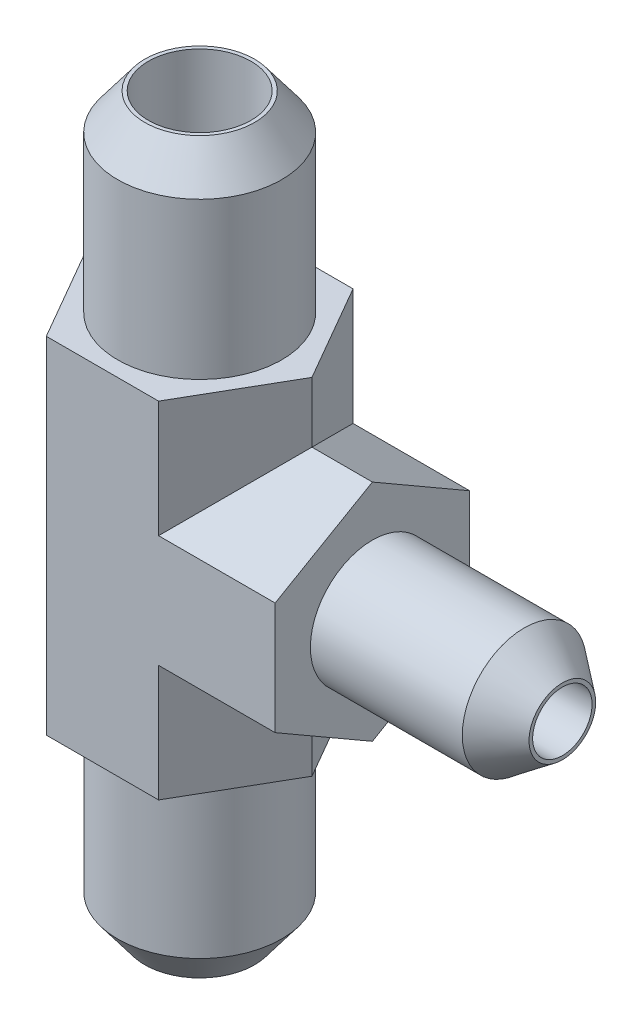
SolidWorks part; units mm, degrees
ref_plane "Front Plane" through (0, 0, 0) normal (0, 0, 1) x (1, 0, 0)
ref_plane "Top Plane" through (0, 0, 0) normal (0, 1, 0) x (1, 0, 0)
ref_plane "Right Plane" through (0, 0, 0) normal (1, 0, 0) x (0, 0, -1)
sketch "Sketch1" plane through (0, 0, 0) normal (0, 1, 0) x (1, 0, 0)
  line L1 (-8.2562, 0) -> (-4.1281, -7.1501)
  line L2 (-4.1281, -7.1501) -> (4.1281, -7.1501)
  line L3 (4.1281, -7.1501) -> (8.2562, 0)
  line L4 (8.2562, 0) -> (4.1281, 7.1501)
  line L5 (4.1281, 7.1501) -> (-4.1281, 7.1501)
  line L6 (-4.1281, 7.1501) -> (-8.2562, 0)
  circle A0 centre (0, 0) radius 7.1501 construction
  dimension "D1" = 14.3002
extrude "Boss-Extrude1" add sketch "Sketch1" along normal mid plane 25.4
sketch "Sketch2" plane through (0, 0, 0) normal (1, 0, 0) x (0, 0, -1)
  line L0 (-7.1501, 12.7) -> (-7.1501, -12.7) construction
  line L1 (0, 8.2562) -> (-7.1501, 4.1281)
  line L2 (-7.1501, 4.1281) -> (-7.1501, -4.1281)
  line L3 (-7.1501, -4.1281) -> (0, -8.2562)
  line L4 (0, -8.2562) -> (7.1501, -4.1281)
  line L5 (7.1501, -4.1281) -> (7.1501, 4.1281)
  line L6 (7.1501, 4.1281) -> (0, 8.2562)
  circle A0 centre (0, 0) radius 7.1501 construction
extrude "Boss-Extrude2" add sketch "Sketch2" along normal blind 12.7
sketch "Sketch3" plane through (12.7, 0, 0) normal (1, 0, 0) x (0, 0, -1)
  circle A0 centre (0, 0) radius 4.5593
  dimension "D1" = 9.1186
extrude "Boss-Extrude3" add sketch "Sketch3" along normal blind 13.97
sketch "Sketch4" plane through (26.67, 0, 0) normal (1, 0, 0) x (0, 0, -1)
  circle A0 centre (0, 0) radius 2.4511
  circle A1 centre (0, 0) radius 11.3639
  dimension "D1" = 4.9022
extrude "Cut-Extrude1" cut sketch "Sketch4" against normal through all draft 37
sketch "Sketch5" plane through (0, -12.7, 0) normal (0, -1, 0) x (1, 0, 0)
  circle A0 centre (0, 0) radius 6.0325
  dimension "D1" = 12.065
extrude "Boss-Extrude4" add sketch "Sketch5" along normal blind 14.1224
sketch "Sketch6" plane through (0, -26.8224, 0) normal (0, -1, 0) x (1, 0, 0)
  circle A0 centre (0, 0) radius 4.0386
  circle A1 centre (0, 0) radius 16.7971
  dimension "D1" = 8.0772
extrude "Cut-Extrude2" cut sketch "Sketch6" against normal through all draft 37
mirror "Mirror1" about plane through (0, 0, 0) normal (0, 1, 0) of "Boss-Extrude4", "Cut-Extrude2"
sketch "Sketch7" plane through (0, -26.8224, 0) normal (0, -1, 0) x (1, 0, 0)
  circle A0 centre (0, 0) radius 3.7719
  dimension "D1" = 7.5438
extrude "Cut-Extrude3" cut sketch "Sketch7" against normal through all
sketch "Sketch8" plane through (26.67, 0, 0) normal (1, 0, 0) x (0, 0, -1)
  circle A0 centre (0, 0) radius 2.1844
  dimension "D1" = 4.3688
extrude "Cut-Extrude4" cut sketch "Sketch8" against normal up to next
